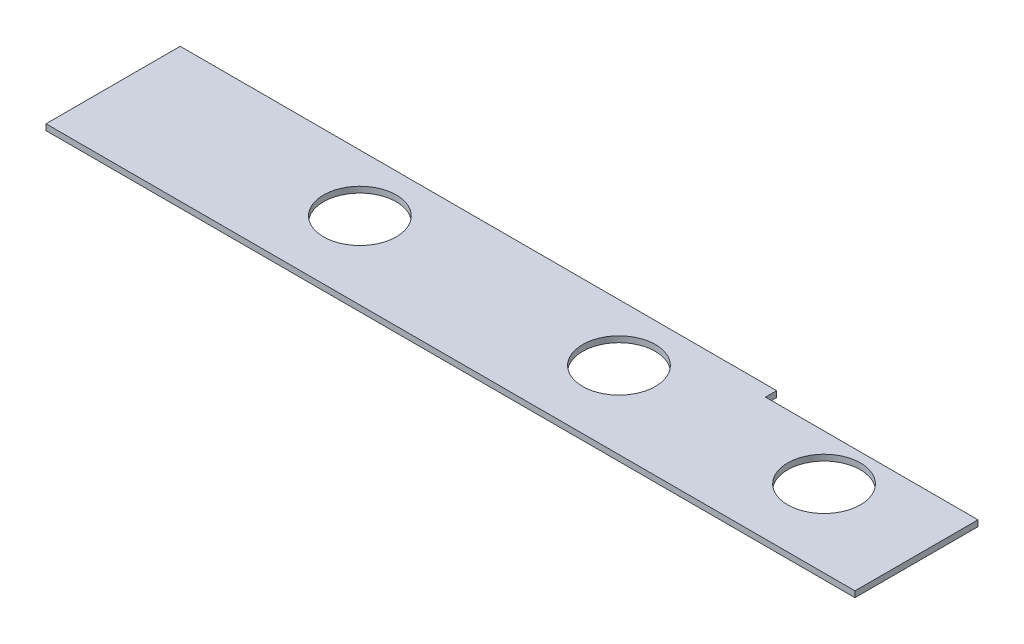
SolidWorks part; units mm, degrees
ref_plane "Front Plane" through (0, 0, 0) normal (0, 0, 1) x (1, 0, 0)
ref_plane "Top Plane" through (0, 0, 0) normal (0, 1, 0) x (1, 0, 0)
ref_plane "Right Plane" through (0, 0, 0) normal (1, 0, 0) x (0, 0, -1)
sketch "Sketch1" plane through (0, 0, 0) normal (0, 1, 0) x (1, 0, 0)
  line L1 (-108.5, -18) -> (108.5, -18) construction
  line L2 (-108.5, -18) -> (-108.5, 18) construction
  line L3 (-108.5, 18) -> (108.5, 18) construction
  line L4 (108.5, -18) -> (108.5, 18) construction
  circle A0 centre (-45, 2.7) radius 10 construction
  circle A1 centre (24.5, 2.7) radius 10 construction
  circle A2 centre (79.5, 2.7) radius 10 construction
  point P0 (0, 0)
  dimension "D3" = 20
  dimension "D4" = 20
  dimension "D5" = 20
  dimension "D1" = 36
  dimension "D2" = 217
  dimension "D6" = 15.3
  dimension "D7" = 15.3
  dimension "D8" = 15.3
  dimension "D9" = 63.5
  dimension "D10" = 133
  dimension "D11" = 188
sketch "Sketch2" plane through (0, 0, 0) normal (0, 1, 0) x (1, 0, 0)
  line L0 (108.5, 15) -> (51.5, 15) construction
  line L1 (-108.5, 18) -> (51.5, 18)
  line L2 (-108.5, 18) -> (-108.5, -18)
  line L3 (-108.5, -18) -> (108.5, -18)
  line L4 (108.5, 15) -> (108.5, -18)
  line L5 (51.5, 15) -> (51.5, 18) construction
  line L6 (51.5, 18) -> (51.5, 15)
  line L7 (51.5, 15) -> (108.5, 15)
  circle A0 centre (-45, 2.7) radius 9.75
  circle A1 centre (24.5, 2.7) radius 9.75
  circle A2 centre (79.5, 2.7) radius 9.75
  dimension "D1" = 19.5
  dimension "D2" = 19.5
  dimension "D3" = 19.5
  dimension "D4" = 57
  dimension "3" = 3
extrude "Boss-Extrude1" add sketch "Sketch2" along normal blind 1.6
